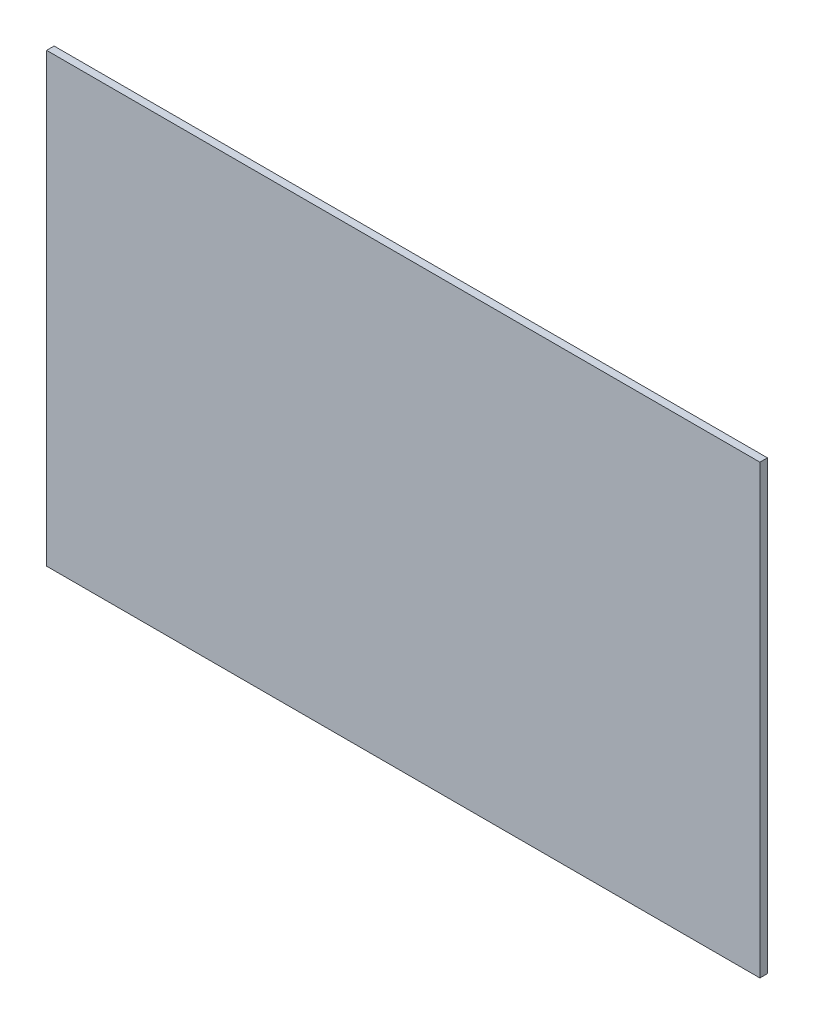
SolidWorks part; units mm, degrees
ref_plane "Спереди" through (0, 0, 0) normal (0, 0, 1) x (1, 0, 0)
ref_plane "Сверху" through (0, 0, 0) normal (0, 1, 0) x (1, 0, 0)
ref_plane "Справа" through (0, 0, 0) normal (1, 0, 0) x (0, 0, -1)
sketch "Эскиз1" plane through (0, 0, 0) normal (0, 0, 1) x (1, 0, 0)
  line L1 (-475, 297.5) -> (475, 297.5)
  line L2 (-475, 297.5) -> (-475, -297.5)
  line L3 (-475, -297.5) -> (475, -297.5)
  line L4 (475, 297.5) -> (475, -297.5)
  line L5 (-475, 297.5) -> (475, -297.5) construction
  line L6 (-475, -297.5) -> (475, 297.5) construction
  point P0 (0, 0)
  dimension "D1" = 595
  dimension "D2" = 950
extrude "Бобышка-Вытянуть1" add sketch "Эскиз1" along normal blind 10
